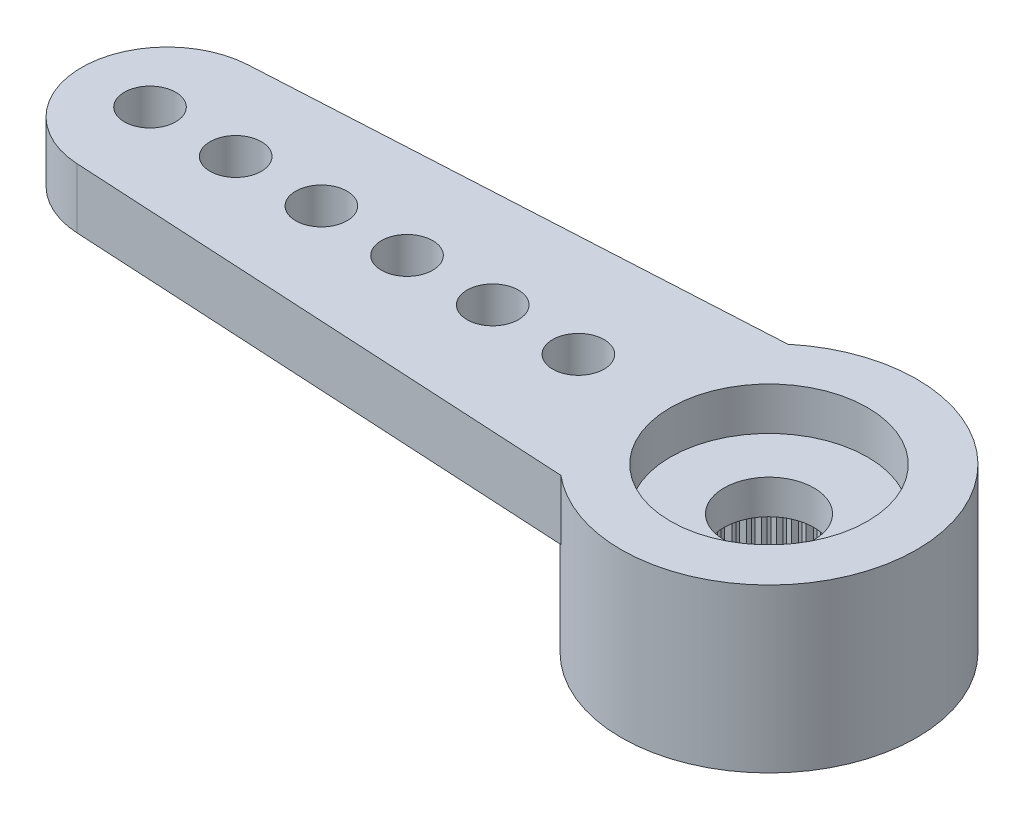
SolidWorks part; units mm, degrees
other "Markup1"
sketch "Sketch1" plane through (-16.05, -3.8, -3.45) normal (-0.0453, -0.05, -0.9977) x (-0.6764, -0.7334, 0.0675)
material "ABS PC"
ref_plane "Plano frontal" through (0, 0, 0) normal (0, 0, 1) x (1, 0, 0)
ref_plane "Plano superior" through (0, 0, 0) normal (0, 1, 0) x (1, 0, 0)
ref_plane "Plano direito" through (0, 0, 0) normal (1, 0, 0) x (0, 0, -1)
sketch "Esboço1" plane through (0, 0, 0) normal (0, 1, 0) x (1, 0, 0)
  line L0 (0, 0) -> (-14.05, 0) construction
  line L1 (-14.1591, 1.997) -> (-2.2091, 2.65)
  line L2 (-2.2091, -2.65) -> (-14.1591, -1.997)
  arc A0 (-2.2091, -2.65) -> (-2.2091, 2.65) centre (0, 0) ccw
  arc A1 (-14.1591, 1.997) -> (-14.1591, -1.997) centre (-14.05, 0) ccw
  dimension "D1" = 6.9
  dimension "D2" = 4
  dimension "D3" = 19.5
  dimension "D4" = 5.3
extrude "Ressalto-extrusão1" add sketch "Esboço1" against normal blind 1.4
sketch "Esboço2" plane through (0, -1.4, 0) normal (0, -1, 0) x (1, 0, 0)
  arc A0 (-2.2091, -2.65) -> (-2.2091, 2.65) centre (0, 0) ccw construction
  circle A1 centre (0, 0) radius 3.45
extrude "Ressalto-extrusão2" add sketch "Esboço2" along normal offset from surface (2.4 mm away) 3.8 up to face at (-7.242, 0, 0)
hole_wizard "Furo4" positions "Esboço9" profile "Esboço10" legacy end condition through all
sketch "Esboço9" plane through (0, 0, 0) normal (0, 1, 0) x (1, 0, 0)
  line L1 (-14.45, 0) -> (0, 0) construction
  arc A2 (-14.1591, 1.997) -> (-14.1591, -1.997) centre (-14.05, 0) ccw construction
  point P0 (-14.45, 0)
  point P19 (-16.05, 0)
  dimension "D1" = 1.6
sketch "Esboço10" plane through (-14.45, 0, 0) normal (1, 0, 0) x (0, 0, 1)
  line L0 (0, 0) -> (0, 3.8)
  line L1 (0, 3.8) -> (0.6, 3.8)
  line L2 (0.6, 3.8) -> (0.6, 0)
  line L3 (0.6, 0) -> (0, 0)
  line L4 (0, 110) -> (0, -10) construction
  dimension "Diameter" = 1.2
  dimension "Depth" = 3.8
pattern_linear "Padrão linear1" count 6 spacing 2 along (1, 0, 0) of "Furo4"
hole_wizard "Furo1" positions "Esboço3" profile "Esboço4" legacy
sketch "Esboço3" plane through (0, -3.8, 0) normal (0, -1, 0) x (-1, 0, 0)
  point P0 (0, 0)
sketch "Esboço4" plane through (0, -3.8, 0) normal (1, 0, 0) x (0, 0, -1)
  line L0 (0, 0) -> (0, 2)
  line L1 (0, 2) -> (2.475, 2)
  line L2 (2.475, 2) -> (2.475, 0)
  line L3 (2.475, 0) -> (0, 0)
  line L4 (0, 110) -> (0, -10) construction
  dimension "Diameter" = 4.95
  dimension "Depth" = 2
hole_wizard "Furo2" positions "Esboço5" profile "Esboço6" legacy
sketch "Esboço5" plane through (0, 0, 0) normal (0, 1, 0) x (1, 0, 0)
  point P0 (0, 0)
sketch "Esboço6" plane through (0, 0, 0) normal (1, 0, 0) x (0, 0, 1)
  line L0 (0, 0) -> (0, 1)
  line L1 (0, 1) -> (2.3, 1)
  line L2 (2.3, 1) -> (2.3, 0)
  line L3 (2.3, 0) -> (0, 0)
  line L4 (0, 110) -> (0, -10) construction
  dimension "Diameter" = 4.6
  dimension "Depth" = 1
hole_wizard "Furo3" positions "Esboço7" profile "Esboço8" legacy end condition through all
sketch "Esboço7" plane through (0, 0, 0) normal (0, 1, 0) x (1, 0, 0)
  point P0 (0, 0)
sketch "Esboço8" plane through (0, 0, 0) normal (1, 0, 0) x (0, 0, 1)
  line L0 (0, 0) -> (0, 3.8)
  line L1 (0, 3.8) -> (1.05, 3.8)
  line L2 (1.05, 3.8) -> (1.05, 0)
  line L3 (1.05, 0) -> (0, 0)
  line L4 (0, 110) -> (0, -10) construction
  dimension "Diameter" = 2.1
  dimension "Depth" = 3.8
sketch "Esboço11" plane through (0, -3.8, 0) normal (0, -1, 0) x (1, 0, 0)
  line L0 (-0.0981, 2.4731) -> (0, 2.375)
  line L1 (0, 2.375) -> (0.0981, 2.4731)
  line L2 (0, 0) -> (0, 2.475) construction
  circle A0 centre (0, 0) radius 2.375 construction
  circle A1 centre (0, 0) radius 2.475
  arc A2 (0.0981, 2.4731) -> (-0.0981, 2.4731) centre (0, 0) ccw
  dimension "D3" = 4.75
  dimension "D2" = 0.1
  dimension "D1" = 0
extrude "Ressalto-extrusão3" add sketch "Esboço11" against normal up to surface (2 mm away) up to face at (0, -1.8, 1.05)
pattern_circular "PadrãoCircular1" count 60 over 360 about axis through (0, 0, 0) along (0, 1, 0) of "Ressalto-extrusão3"
